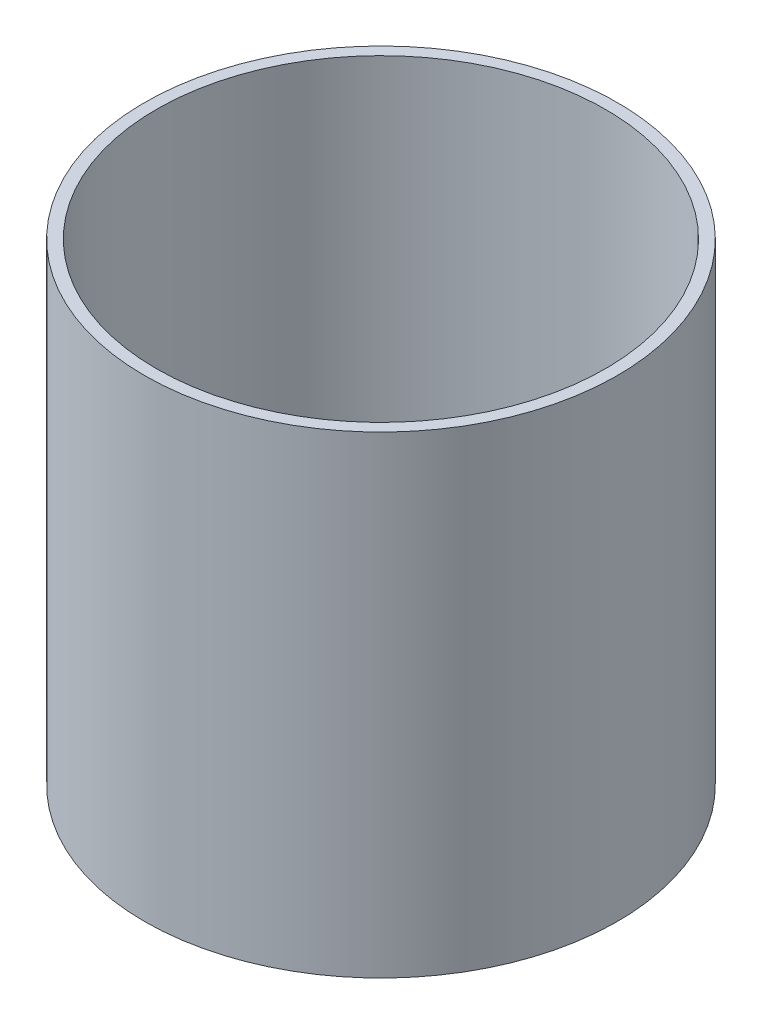
SolidWorks part; units mm, degrees
ref_plane "Front Plane" through (0, 0, 0) normal (0, 0, 1) x (1, 0, 0)
ref_plane "Top Plane" through (0, 0, 0) normal (0, 1, 0) x (1, 0, 0)
ref_plane "Right Plane" through (0, 0, 0) normal (1, 0, 0) x (0, 0, -1)
sketch "Sketch1" plane through (0, 0, 0) normal (0, 1, 0) x (1, 0, 0)
  circle A0 centre (-36.4029, 20.2238) radius 50
  dimension "D1" = 100
extrude "Boss-Extrude1" add sketch "Sketch1" along normal blind 100
sketch "Sketch2" plane through (0, 100, 0) normal (0, 1, 0) x (1, 0, 0)
  circle A0 centre (-36.4029, 20.2238) radius 47.5
  circle A1 centre (-36.4029, 20.2238) radius 50 construction
  dimension "D1" = 0
  dimension "D2" = 95
extrude "Cut-Extrude1" cut sketch "Sketch2" against normal blind 95
